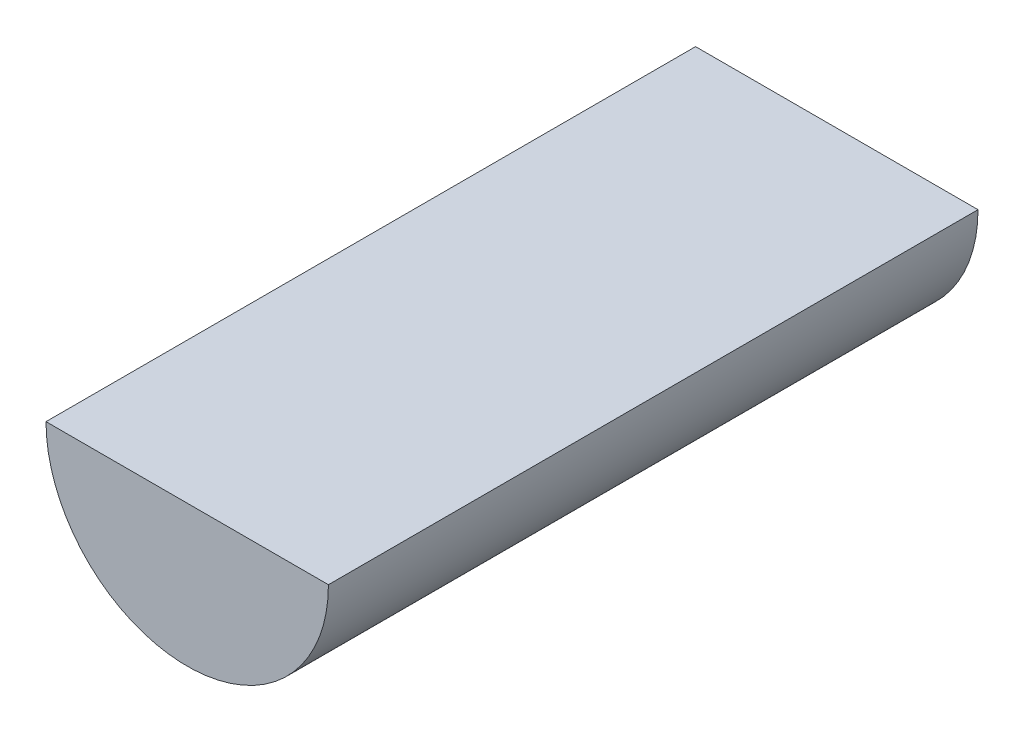
SolidWorks part; units mm, degrees
ref_plane "Front" through (0, 0, 0) normal (0, 0, 1) x (1, 0, 0)
ref_plane "Top" through (0, 0, 0) normal (0, 1, 0) x (1, 0, 0)
ref_plane "Right" through (0, 0, 0) normal (1, 0, 0) x (0, 0, -1)
sketch "Sketch1" plane through (0, 0, 0) normal (0, 0, 1) x (1, 0, 0)
  line L0 (-50, 0) -> (50, 0)
  line L1 (0, -50) -> (0, 0) construction
  arc A0 (-50, 0) -> (50, 0) centre (0, 0) ccw
  dimension "D1" = 100
  dimension "D2" = 50
extrude "Boss-Extrude1" add sketch "Sketch1" along normal blind 230
